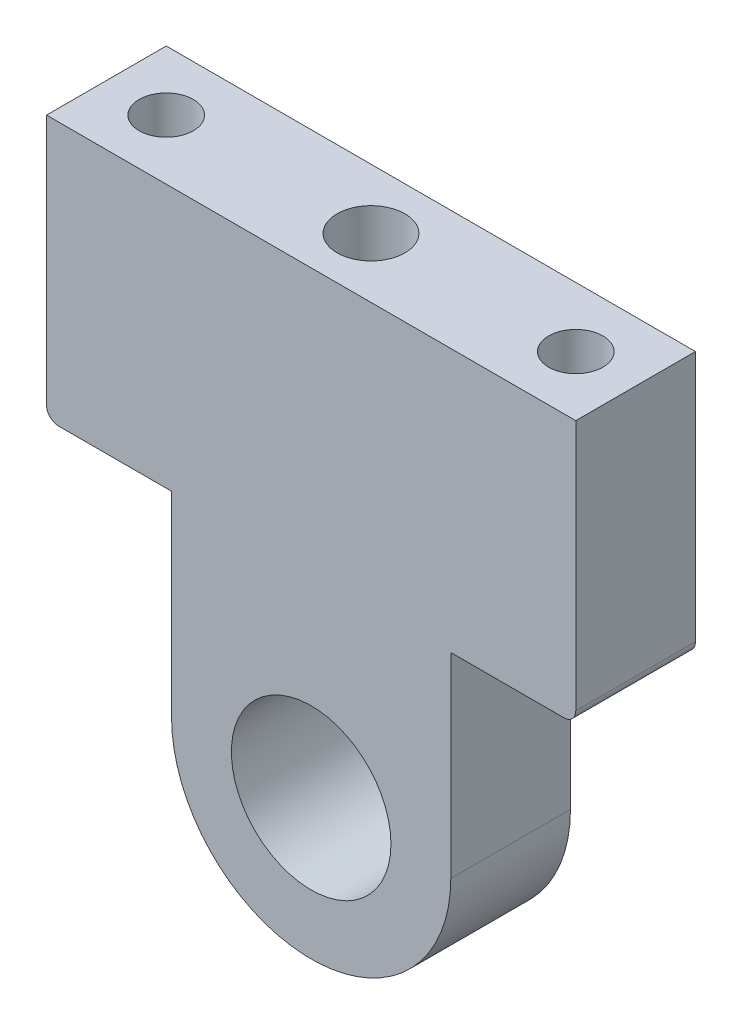
SolidWorks part; units mm, degrees
ref_plane "Front Plane" through (0, 0, 0) normal (0, 0, 1) x (1, 0, 0)
ref_plane "Top Plane" through (0, 0, 0) normal (0, 1, 0) x (1, 0, 0)
ref_plane "Right Plane" through (0, 0, 0) normal (1, 0, 0) x (0, 0, -1)
sketch "Sketch1" plane through (0, 0, 0) normal (0, 0, 1) x (1, 0, 0)
  line L0 (33.165, 33) -> (33.165, -24.529) construction
  line L1 (0, 0) -> (66.33, 0) construction
  line L2 (0, 0) -> (0, 33)
  line L3 (0, 33) -> (66.33, 33)
  line L4 (66.33, 0) -> (66.33, 33)
  line L5 (15.665, 0) -> (50.665, 0) construction
  line L6 (15.665, 0) -> (15.665, -24.529)
  line L7 (15.665, -24.529) -> (50.665, -24.529) construction
  line L8 (50.665, 0) -> (50.665, -24.529)
  line L9 (0, 0) -> (15.665, 0)
  line L10 (50.665, 0) -> (66.33, 0)
  arc A0 (15.665, -24.529) -> (50.665, -24.529) centre (33.165, -24.529) ccw
  circle A1 centre (33.165, -24.529) radius 10
  point P9 (33.165, -24.529)
  dimension "D5" = 20
  dimension "D6" = 17.5
  dimension "D1" = 66.33
  dimension "D2" = 33
  dimension "D3" = 35
  dimension "D4" = 24.529
extrude "Boss-Extrude1" add sketch "Sketch1" along normal blind 15
sketch "Sketch2" plane through (0, 33, 0) normal (0, 1, 0) x (1, 0, 0)
  line L0 (66.33, 0) -> (0, 0) construction
  line L1 (33.165, 0) -> (33.165, -15) construction
  line L2 (66.33, -15) -> (0, -15) construction
  line L3 (58.831, 0) -> (58.831, -15) construction
  circle A0 centre (33.165, -7.5) radius 4.25 construction
  circle A1 centre (58.831, -7.5) radius 3.4
  circle A2 centre (7.499, -7.5) radius 3.4
  dimension "D2" = 8.5
  dimension "D3" = 6.8
  dimension "D1" = 25.666
extrude "Cut-Extrude1" cut sketch "Sketch2" against normal blind 54
sketch "Sketch3" plane through (0, 33, 0) normal (0, 1, 0) x (1, 0, 0)
  circle A0 centre (33.165, -7.5) radius 4.25
extrude "Cut-Extrude2" cut sketch "Sketch3" against normal blind 28
ref_plane "Plane2" through (15.665, -24.529, 0) normal (0, -1, 0) x (-1, 0, 0)
fillet "Fillet1" radius 1.5 2 edges at (66.33, 0, 7.5) (0, 0, 7.5)
